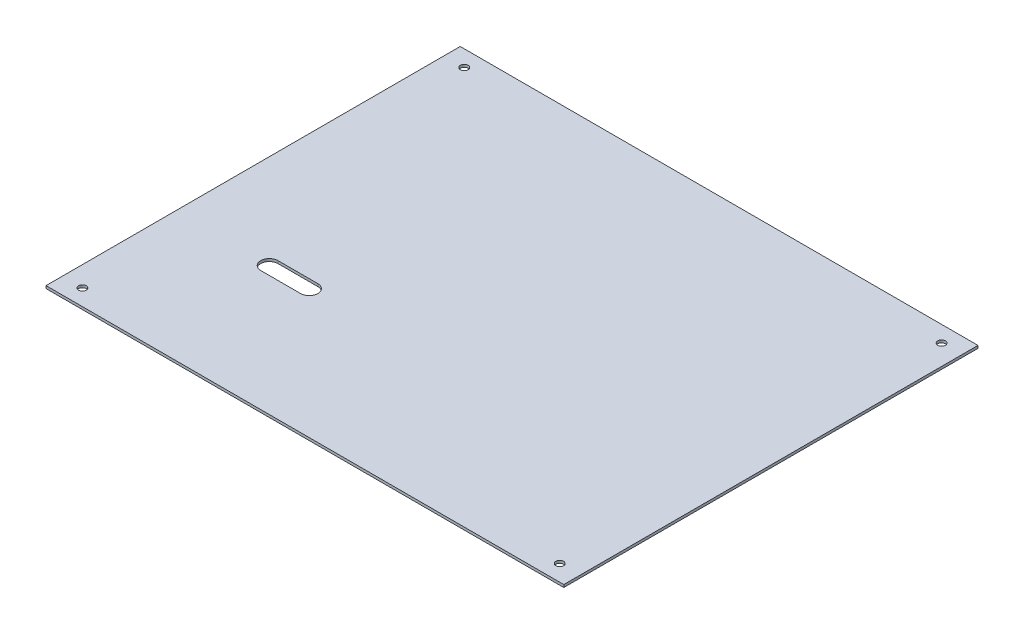
SolidWorks part; units mm, degrees
material "Epoxy, Unfilled"
ref_plane "Front Plane" through (0, 0, 0) normal (0, 0, 1) x (1, 0, 0)
ref_plane "Top Plane" through (0, 0, 0) normal (0, 1, 0) x (1, 0, 0)
ref_plane "Right Plane" through (0, 0, 0) normal (1, 0, 0) x (0, 0, -1)
sketch "Sketch1" plane through (0, 0, 0) normal (0, 1, 0) x (1, 0, 0)
  line L0 (-48.1632, -30.1577) -> (-63.5602, -30.1577) construction
  line L1 (-100, -80) -> (100, -80)
  line L2 (-100, -80) -> (-100, 80)
  line L3 (-100, 80) -> (100, 80)
  line L4 (100, -80) -> (100, 80)
  line L5 (-100, -80) -> (100, 80) construction
  line L6 (-100, 80) -> (100, -80) construction
  line L7 (-48.1632, -33.4797) -> (-63.5602, -33.4797)
  line L8 (-48.1632, -26.8357) -> (-63.5602, -26.8357)
  circle A0 centre (-92.1913, 73.753) radius 1.5
  circle A1 centre (92.1913, 73.753) radius 1.5
  circle A2 centre (92.1913, -73.753) radius 1.5
  circle A3 centre (-92.1913, -73.753) radius 1.5
  arc A4 (-48.1632, -33.4797) -> (-48.1632, -26.8357) centre (-48.1632, -30.1577) ccw
  arc A5 (-63.5602, -26.8357) -> (-63.5602, -33.4797) centre (-63.5602, -30.1577) ccw
  point P0 (0, 0)
  point P16 (-55.8617, -30.1577)
  dimension "D3" = 3
  dimension "D4" = 10
  dimension "D5" = 10
  dimension "D6" = 10
  dimension "D7" = 10
  dimension "D1" = 200
  dimension "D2" = 160
extrude "Boss-Extrude1" add sketch "Sketch1" along normal blind 1
